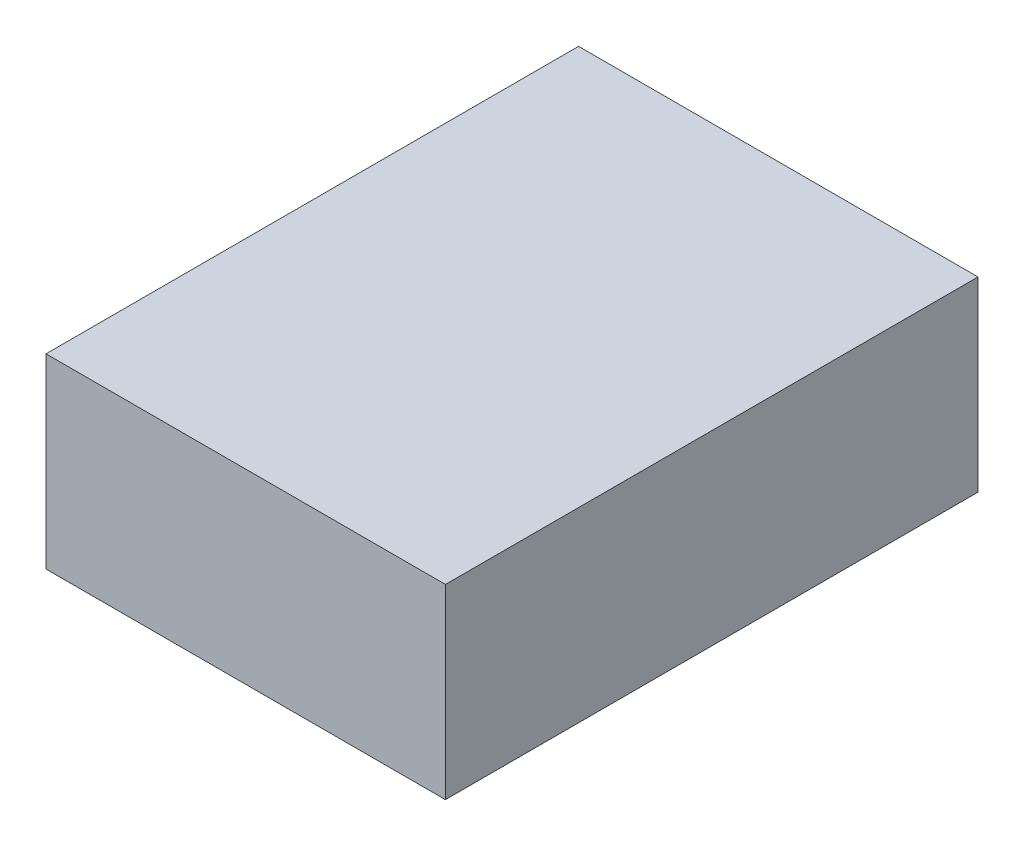
SolidWorks part; units mm, degrees
ref_plane "Front Plane" through (0, 0, 0) normal (0, 0, 1) x (1, 0, 0)
ref_plane "Top Plane" through (0, 0, 0) normal (0, 1, 0) x (1, 0, 0)
ref_plane "Right Plane" through (0, 0, 0) normal (1, 0, 0) x (0, 0, -1)
sketch "Sketch1" plane through (0, 0, 0) normal (0, 1, 0) x (1, 0, 0)
  line L1 (-75, 100) -> (75, 100)
  line L2 (-75, 100) -> (-75, -100)
  line L3 (-75, -100) -> (75, -100)
  line L4 (75, 100) -> (75, -100)
  line L5 (-75, 100) -> (75, -100) construction
  line L6 (-75, -100) -> (75, 100) construction
  point P0 (0, 0)
  dimension "D1" = 200
  dimension "D2" = 150
extrude "Boss-Extrude1" add sketch "Sketch1" along normal blind 70
